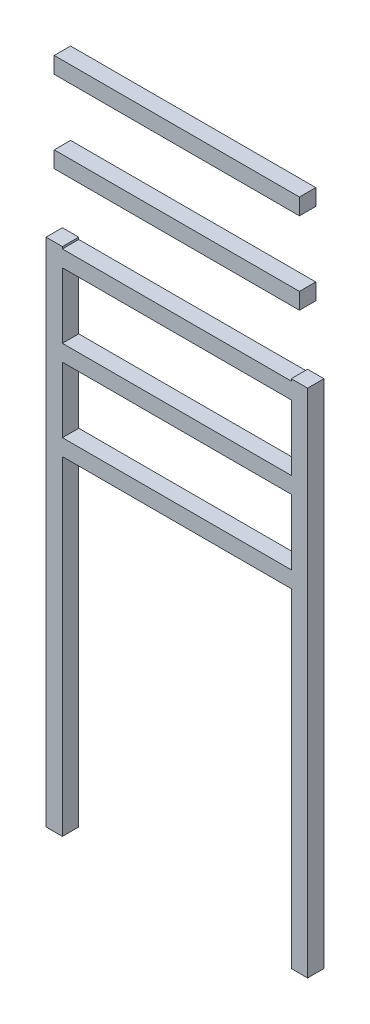
SolidWorks part; units mm, degrees
ref_plane "前视基准面" through (0, 0, 0) normal (0, 0, 1) x (1, 0, 0)
ref_plane "上视基准面" through (0, 0, 0) normal (0, 1, 0) x (1, 0, 0)
ref_plane "右视基准面" through (0, 0, 0) normal (1, 0, 0) x (0, 0, -1)
other "Configuration Table"
sketch "草图1" plane through (0, 0, 0) normal (0, 0, 1) x (1, 0, 0)
  line L1 (-640, -1250) -> (-560, -1250)
  line L2 (-640, -1250) -> (-640, 1250)
  line L3 (-640, 1250) -> (-560, 1250)
  line L4 (-560, -1250) -> (-560, 1250)
  line L5 (-640, -1250) -> (-560, 1250) construction
  line L6 (-640, 1250) -> (-560, -1250) construction
  point P0 (-600, 0)
extrude "凸台-拉伸1" add sketch "草图1" along normal blind 80
sketch "草图2" plane through (0, 0, 0) normal (0, 0, 1) x (1, 0, 0)
  line L1 (560, -1250) -> (640, -1250)
  line L2 (560, -1250) -> (560, 1250)
  line L3 (560, 1250) -> (640, 1250)
  line L4 (640, -1250) -> (640, 1250)
  line L5 (560, -1250) -> (640, 1250) construction
  line L6 (560, 1250) -> (640, -1250) construction
  point P0 (600, 0)
extrude "凸台-拉伸2" add sketch "草图2" along normal blind 80
sketch "草图3" plane through (0, 0, 0) normal (0, 0, 1) x (1, 0, 0)
  line L1 (-600, 360) -> (600, 360)
  line L2 (-600, 360) -> (-600, 440)
  line L3 (-600, 440) -> (600, 440)
  line L4 (600, 360) -> (600, 440)
  line L5 (-600, 360) -> (600, 440) construction
  line L6 (-600, 440) -> (600, 360) construction
  point P0 (0, 400)
extrude "凸台-拉伸3" add sketch "草图3" along normal blind 80
sketch "草图4" plane through (0, 0, 0) normal (0, 0, 1) x (1, 0, 0)
  line L1 (-600, 760) -> (600, 760)
  line L2 (-600, 760) -> (-600, 840)
  line L3 (-600, 840) -> (600, 840)
  line L4 (600, 760) -> (600, 840)
  line L5 (-600, 760) -> (600, 840) construction
  line L6 (-600, 840) -> (600, 760) construction
  point P0 (0, 800)
extrude "凸台-拉伸4" add sketch "草图4" along normal blind 80
sketch "草图5" plane through (0, 0, 0) normal (0, 0, 1) x (1, 0, 0)
  line L1 (-600, 1160) -> (600, 1160)
  line L2 (-600, 1160) -> (-600, 1240)
  line L3 (-600, 1240) -> (600, 1240)
  line L4 (600, 1160) -> (600, 1240)
  line L5 (-600, 1160) -> (600, 1240) construction
  line L6 (-600, 1240) -> (600, 1160) construction
  point P0 (0, 1200)
extrude "凸台-拉伸5" add sketch "草图5" along normal blind 80
sketch "草图6" plane through (0, 0, 0) normal (0, 0, 1) x (1, 0, 0)
  line L1 (-600, 1560) -> (600, 1560)
  line L2 (-600, 1560) -> (-600, 1640)
  line L3 (-600, 1640) -> (600, 1640)
  line L4 (600, 1560) -> (600, 1640)
  line L5 (-600, 1560) -> (600, 1640) construction
  line L6 (-600, 1640) -> (600, 1560) construction
  point P0 (0, 1600)
extrude "凸台-拉伸6" add sketch "草图6" along normal blind 80
sketch "草图7" plane through (0, 0, 0) normal (0, 0, 1) x (1, 0, 0)
  line L1 (-600, 1960) -> (600, 1960)
  line L2 (-600, 1960) -> (-600, 2040)
  line L3 (-600, 2040) -> (600, 2040)
  line L4 (600, 1960) -> (600, 2040)
  line L5 (-600, 1960) -> (600, 2040) construction
  line L6 (-600, 2040) -> (600, 1960) construction
  point P0 (0, 2000)
extrude "凸台-拉伸7" add sketch "草图7" along normal blind 80
